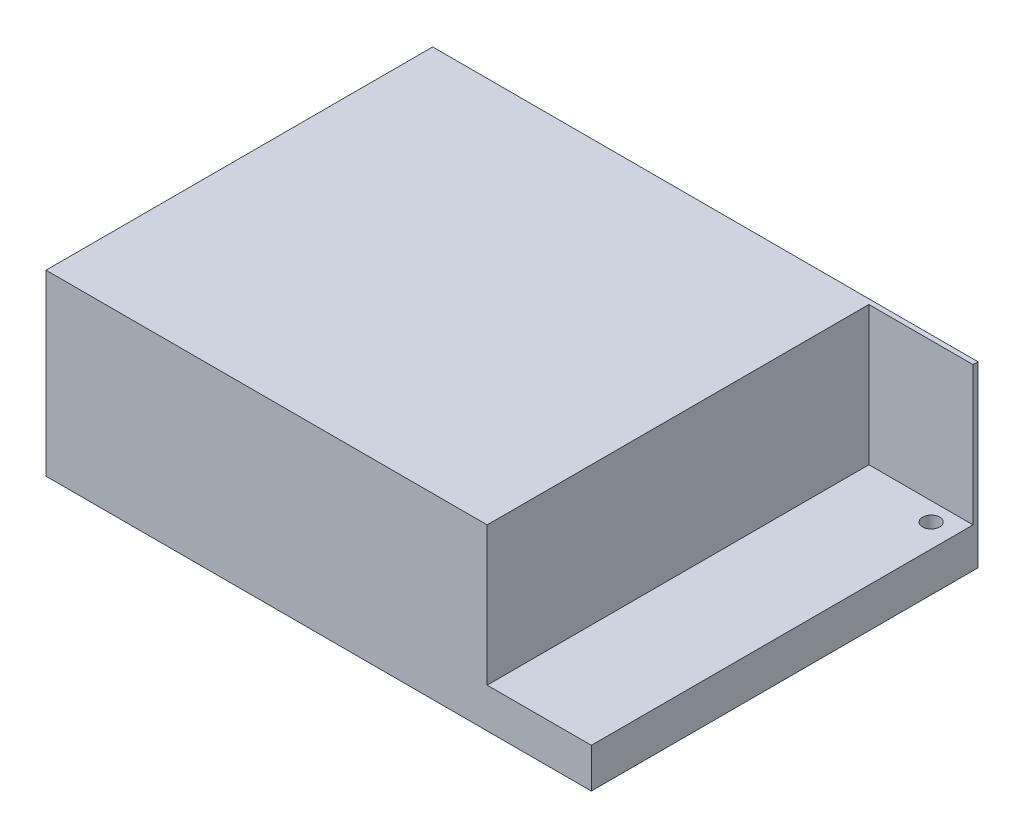
SolidWorks part; units mm, degrees
ref_plane "Front Plane" through (0, 0, 0) normal (0, 0, 1) x (1, 0, 0)
ref_plane "Top Plane" through (0, 0, 0) normal (0, 1, 0) x (1, 0, 0)
ref_plane "Right Plane" through (0, 0, 0) normal (1, 0, 0) x (0, 0, -1)
sketch "Sketch1" plane through (0, 0, 0) normal (0, 1, 0) x (1, 0, 0)
  line L1 (-46.9118, 22.9706) -> (63.0882, 22.9706)
  line L2 (-46.9118, 22.9706) -> (-46.9118, -55.0294)
  line L3 (-46.9118, -55.0294) -> (63.0882, -55.0294)
  line L4 (63.0882, 22.9706) -> (63.0882, -55.0294)
  dimension "D1" = 110
  dimension "D2" = 78
extrude "Boss-Extrude1" add sketch "Sketch1" along normal blind 36
sketch "Sketch2" plane through (0, 36, 0) normal (0, 1, 0) x (1, 0, 0)
  line L0 (63.0882, -55.0294) -> (63.0882, 22.9706) construction
  line L1 (42.0781, 21.9706) -> (63.0882, 21.9706)
  line L2 (42.0781, 21.9706) -> (42.0781, -55.0294)
  line L3 (42.0781, -55.0294) -> (63.0882, -55.0294)
  line L4 (63.0882, 21.9706) -> (63.0882, -55.0294)
  line L5 (-46.9118, -55.0294) -> (63.0882, -55.0294) construction
  line L6 (63.0882, 22.9706) -> (-46.9118, 22.9706) construction
  dimension "D1" = 1
extrude "Cut-Extrude1" cut sketch "Sketch2" against normal offset from surface (28 mm away) 8 up to face at (8.0882, 0, 16.0294)
sketch "Sketch3" plane through (0, 8, 0) normal (0, 1, 0) x (1, 0, 0)
  line L0 (63.0882, 22.9706) -> (-46.9118, 22.9706) construction
  line L1 (63.0882, 21.9706) -> (63.0882, -55.0294) construction
  circle A0 centre (58.3632, 18.2456) radius 1.725
  point P2 (58.3632, 19.9706)
  point P3 (60.0882, 18.2456)
  dimension "D1" = 3.45
  dimension "D2" = 3
  dimension "D3" = 3
extrude "Cut-Extrude2" cut sketch "Sketch3" against normal through all
sketch "Sketch4" plane through (0, 0, 0) normal (0, -1, 0) x (1, 0, 0)
  line L0 (63.0882, 55.0294) -> (63.0882, -22.9706) construction
  line L1 (63.0882, -22.9706) -> (-46.9118, -22.9706) construction
  circle A0 centre (-4.9118, 2.1294) radius 1.5
  circle A1 centre (-4.9118, 30.7294) radius 1.5
  circle A2 centre (30.8382, 30.7294) radius 1.5
  point P6 (29.3382, 30.7294)
  point P7 (-3.4118, 30.7294)
  point P8 (-4.9118, 32.2294)
  point P9 (-4.9118, 3.6294)
  point P10 (-3.4118, 2.1294)
  point P11 (-4.9118, 0.6294)
  point P12 (-4.9118, 29.2294)
  dimension "D2" = 3
  dimension "D1" = 25.6
  dimension "D3" = 32.75
  dimension "D4" = 66.5
  dimension "D5" = 23.6
extrude "Cut-Extrude3" cut sketch "Sketch4" against normal blind 5
